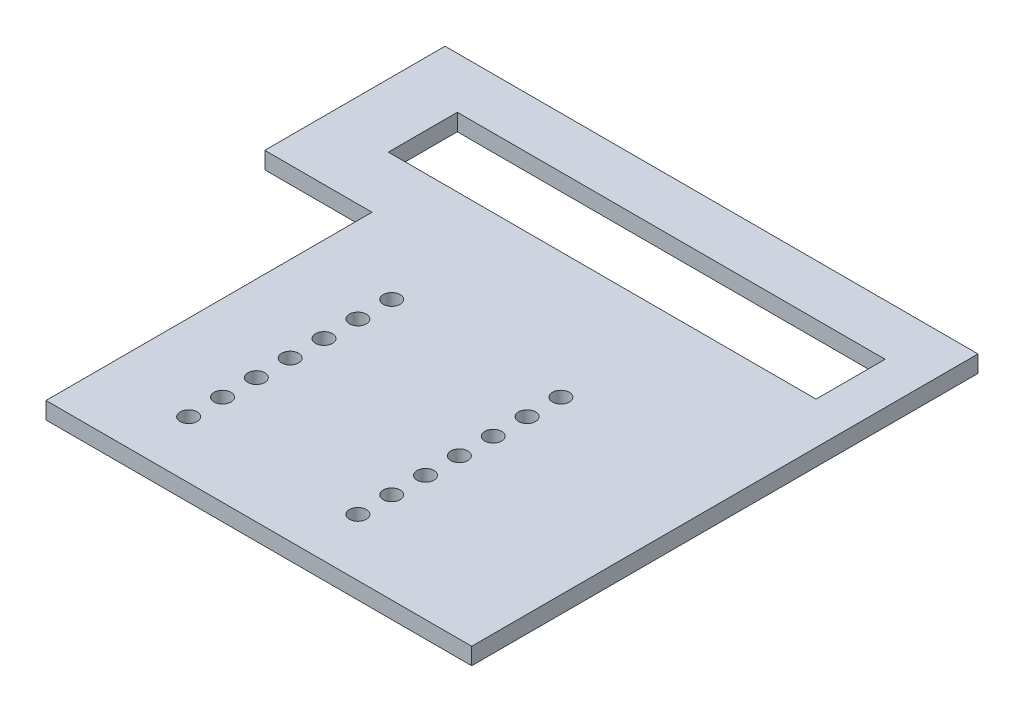
SolidWorks part; units mm, degrees
ref_plane "Front Plane" through (0, 0, 0) normal (0, 0, 1) x (1, 0, 0)
ref_plane "Top Plane" through (0, 0, 0) normal (0, 1, 0) x (1, 0, 0)
ref_plane "Right Plane" through (0, 0, 0) normal (1, 0, 0) x (0, 0, -1)
sketch "Sketch1" plane through (0, 0, 0) normal (0, 1, 0) x (1, 0, 0)
  line L0 (0, -112.5) -> (0, 0) construction
  line L1 (-80, 112.5) -> (100, 112.5)
  line L3 (-80, -112.5) -> (100, -112.5)
  line L4 (100, 112.5) -> (100, -112.5)
  line L5 (0, 0) -> (0, 112.5) construction
  arc A0 (-80, 112.5) -> (-80, -112.5) centre (-80, 0) ccw
  dimension "D1" = 100
  dimension "D4" = 112.5
  dimension "D2" = 80
  dimension "D3" = 225
extrude "Boss-Extrude1" add sketch "Sketch1" against normal blind 3.175
sketch "Sketch2" plane through (0, 0, 0) normal (0, 1, 0) x (1, 0, 0)
  line L0 (36.144, -66.3448) -> (36.144, -59.9948) construction
  line L1 (52.019, 0) -> (52.019, -89.9668) construction
  line L2 (11.887, -89.9668) -> (92.151, -89.9668)
  line L3 (11.887, -89.9668) -> (11.887, -102.9208)
  line L4 (11.887, -102.9208) -> (92.151, -102.9208)
  line L5 (92.151, -89.9668) -> (92.151, -102.9208)
  line L6 (11.887, 89.9668) -> (92.151, 89.9668)
  line L7 (11.887, 89.9668) -> (11.887, 102.9208)
  line L8 (11.887, 102.9208) -> (92.151, 102.9208)
  line L9 (92.151, 89.9668) -> (92.151, 102.9208)
  line L10 (52.019, 0) -> (52.019, 89.9668) construction
  line L11 (36.144, -59.9948) -> (36.144, -53.6448) construction
  line L12 (36.144, -53.6448) -> (36.144, -47.2948) construction
  line L13 (36.144, -47.2948) -> (36.144, -40.9448) construction
  line L14 (36.144, -40.9448) -> (36.144, -34.5948) construction
  line L15 (36.144, -34.5948) -> (36.144, -28.2448) construction
  line L16 (67.894, -66.3448) -> (67.894, -59.9948) construction
  line L17 (67.894, -59.9948) -> (67.894, -53.6448) construction
  line L18 (67.894, -53.6448) -> (67.894, -47.2948) construction
  line L19 (67.894, -47.2948) -> (67.894, -40.9448) construction
  line L20 (67.894, -40.9448) -> (67.894, -34.5948) construction
  line L21 (67.894, -34.5948) -> (67.894, -28.2448) construction
  line L22 (36.144, -66.3448) -> (67.894, -66.3448) construction
  line L23 (36.144, -28.2448) -> (67.894, -28.2448) construction
  line L24 (36.144, 28.2448) -> (36.144, 34.5948) construction
  line L25 (36.144, 34.5948) -> (36.144, 40.9448) construction
  line L26 (36.144, 40.9448) -> (36.144, 47.2948) construction
  line L27 (36.144, 47.2948) -> (36.144, 53.6448) construction
  line L28 (36.144, 53.6448) -> (36.144, 59.9948) construction
  line L29 (36.144, 59.9948) -> (36.144, 66.3448) construction
  line L30 (67.894, 28.2448) -> (67.894, 34.5948) construction
  line L31 (67.894, 34.5948) -> (67.894, 40.9448) construction
  line L32 (67.894, 40.9448) -> (67.894, 47.2948) construction
  line L33 (67.894, 47.2948) -> (67.894, 53.6448) construction
  line L34 (67.894, 53.6448) -> (67.894, 59.9948) construction
  line L35 (67.894, 59.9948) -> (67.894, 66.3448) construction
  line L36 (36.144, 66.3448) -> (67.894, 66.3448) construction
  line L37 (36.144, 28.2448) -> (67.894, 28.2448) construction
  line L38 (36.144, 47.2948) -> (52.019, 47.2948) construction
  line L39 (52.019, 47.2948) -> (67.894, 47.2948) construction
  line L40 (0, -112.5) -> (0, 112.5) construction
  line L41 (0, 0) -> (52.019, 0) construction
  line L42 (100, 112.5) -> (-80, 112.5) construction
  line L43 (-80, -112.5) -> (100, -112.5) construction
  circle A1 centre (36.144, -66.3448) radius 1.5875
  circle A2 centre (36.144, -59.9948) radius 1.5875
  circle A3 centre (36.144, -53.6448) radius 1.5875
  circle A4 centre (36.144, -47.2948) radius 1.5875
  circle A5 centre (36.144, -40.9448) radius 1.5875
  circle A6 centre (36.144, -34.5948) radius 1.5875
  circle A7 centre (36.144, -28.2448) radius 1.5875
  circle A8 centre (67.894, -66.3448) radius 1.5875
  circle A9 centre (67.894, -59.9948) radius 1.5875
  circle A10 centre (67.894, -53.6448) radius 1.5875
  circle A11 centre (67.894, -47.2948) radius 1.5875
  circle A12 centre (67.894, -40.9448) radius 1.5875
  circle A13 centre (67.894, -34.5948) radius 1.5875
  circle A14 centre (67.894, -28.2448) radius 1.5875
  circle A15 centre (36.144, 66.3448) radius 1.5875
  circle A16 centre (36.144, 59.9948) radius 1.5875
  circle A17 centre (36.144, 53.6448) radius 1.5875
  circle A18 centre (36.144, 47.2948) radius 1.5875
  circle A19 centre (36.144, 40.9448) radius 1.5875
  circle A20 centre (36.144, 34.5948) radius 1.5875
  circle A21 centre (36.144, 28.2448) radius 1.5875
  circle A22 centre (67.894, 66.3448) radius 1.5875
  circle A23 centre (67.894, 59.9948) radius 1.5875
  circle A24 centre (67.894, 53.6448) radius 1.5875
  circle A25 centre (67.894, 47.2948) radius 1.5875
  circle A26 centre (67.894, 40.9448) radius 1.5875
  circle A27 centre (67.894, 34.5948) radius 1.5875
  circle A28 centre (67.894, 28.2448) radius 1.5875
  dimension "D6" = 3.175
  dimension "D7" = 6.35
  dimension "D8" = 15.875
  dimension "D10" = 3.175
  dimension "D1" = 12.954
  dimension "D2" = 80.264
  dimension "D3" = 179.9336
  dimension "D4" = 23.622
  dimension "D5" = 15.875
  dimension "D9" = 15.875
  dimension "D11" = 6.35
  dimension "D12" = 23.622
  dimension "D13" = 56.4896
  dimension "D14" = 205.8416
  dimension "D15" = 92.151
extrude "Cut-Extrude1" cut sketch "Sketch2" against normal through all
sketch "Sketch7" plane through (0, 0, 0) normal (0, 1, 0) x (1, 0, 0)
  line L0 (10, 112.5) -> (9.5225, 69.596) construction
  line L1 (-37.7215, 69.596) -> (9.5225, 69.596)
  line L2 (-37.7215, 69.596) -> (-37.7215, -69.596)
  line L3 (-37.7215, -69.596) -> (9.5225, -69.596)
  line L4 (9.5225, 69.596) -> (9.5225, -69.596)
  line L5 (100, 112.5) -> (-80, 112.5) construction
  line L6 (9.5225, -69.596) -> (10, -112.5) construction
  line L7 (-80, -112.5) -> (100, -112.5) construction
  line L8 (-50.4215, -40.64) -> (-50.4215, 0) construction
  line L9 (-50.4215, 0) -> (-50.4215, 40.64) construction
  circle A0 centre (-50.4215, 0) radius 2.032
  circle A1 centre (25.7785, 0) radius 1.651
  circle A2 centre (86.7385, 0) radius 1.651
  circle A3 centre (-50.4215, 40.64) radius 1.651
  circle A4 centre (-50.4215, -40.64) radius 1.651
  circle A5 centre (15.8725, -40.64) radius 2.032
  circle A6 centre (15.8725, 40.64) radius 2.032
  dimension "D3" = 4.064
  dimension "D5" = 40.64
  dimension "D9" = 3.302
  dimension "D10" = 3.302
  dimension "D11" = 3.302
  dimension "D12" = 4.064
  dimension "D13" = 4.064
  dimension "D1" = 47.244
  dimension "D2" = 139.192
  dimension "D4" = 12.7
  dimension "D6" = 6.35
  dimension "D7" = 16.256
  dimension "D8" = 60.96
extrude "Cut-Extrude4" cut sketch "Sketch7" against normal through all
sketch "Sketch8" plane through (0, 0, 0) normal (0, 1, 0) x (1, 0, 0)
  line L0 (-80, 112.5) -> (-80, -112.5) construction
  line L1 (-192.5, 0) -> (100, 0) construction
  line L2 (100, -112.5) -> (100, 112.5) construction
  line L3 (-167.0966, 25.4) -> (-229.7767, 25.4)
  line L4 (-229.7767, 25.4) -> (-229.7767, -25.4)
  line L5 (-229.7767, -25.4) -> (-167.0966, -25.4)
  line L6 (-182.2096, 12.065) -> (-182.2096, -12.065) construction
  line L7 (-182.2096, -12.065) -> (-151.9836, -12.065) construction
  line L8 (-151.9836, -12.065) -> (-151.9836, 12.065) construction
  line L9 (-151.9836, 12.065) -> (-182.2096, 12.065) construction
  arc A0 (-80, 112.5) -> (-80, -112.5) centre (-80, 0) ccw construction
  circle A1 centre (-177.3836, 33.02) radius 1.651
  arc A2 (-167.0966, 25.4) -> (-167.0966, -25.4) centre (-167.0966, 0) cw
  circle A3 centre (-177.3836, -33.02) radius 1.651
  circle A4 centre (-151.9836, 33.02) radius 1.651
  circle A5 centre (-151.9836, -33.02) radius 1.651
  point P12 (-80, 0)
  point P19 (-151.9836, 0)
  point P22 (-167.0966, 12.065)
  dimension "D2" = 87.0966
  dimension "D1" = 25.4
  dimension "D6" = 33.02
  dimension "D11" = 3.302
  dimension "D3" = 112.5
  dimension "D4" = 30.226
  dimension "D5" = 24.13
  dimension "D7" = 33.02
  dimension "D8" = 33.02
  dimension "D9" = 33.02
  dimension "D10" = 25.4
extrude "Cut-Extrude5" cut sketch "Sketch8" against normal through all
sketch "Sketch9" plane through (0, 0, 0) normal (0, 1, 0) x (1, 0, 0)
  line L0 (-161.7953, 55.88) -> (-124.9646, 86.7846) construction
  line L1 (-161.7953, -55.88) -> (-124.9646, -86.7846) construction
  line L2 (-161.7953, -55.88) -> (-125.8605, -55.88) construction
  line L3 (-161.7953, 55.88) -> (-125.8605, 55.88) construction
  circle A0 centre (-161.7953, -55.88) radius 1.778
  circle A1 centre (-124.9646, -86.7846) radius 1.778
  circle A2 centre (-161.7953, 55.88) radius 1.778
  circle A3 centre (-124.9646, 86.7846) radius 1.778
  arc A4 (-167.0966, -25.4) -> (-167.0966, 25.4) centre (-167.0966, 0) ccw construction
  point P8 (-141.6966, 0)
  point P14 (-141.6966, 0)
  dimension "D5" = 3.556
  dimension "D1" = 40
  dimension "D2" = 40
  dimension "D3" = 55.88
  dimension "D4" = 55.88
extrude "Cut-Extrude6" cut sketch "Sketch9" against normal through all
sketch "Sketch10" plane through (0, 0, 0) normal (0, 1, 0) x (1, 0, 0)
  line L0 (0, 127.9795) -> (0, 78.6728)
  line L1 (0, 78.6728) -> (20.1251, 78.6728)
  line L2 (20.1251, 78.6728) -> (20.1251, 17.4997)
  line L3 (20.1251, 17.4997) -> (114.9924, 17.4997)
  line L4 (114.9924, 17.4997) -> (114.9924, -151.1439)
  line L5 (114.9924, -151.1439) -> (-214.2597, -151.1439)
  line L6 (-214.2597, -151.1439) -> (-214.2597, 127.9795)
  line L7 (-214.2597, 127.9795) -> (0, 127.9795)
extrude "Cut-Extrude7" cut sketch "Sketch10" against normal through all
